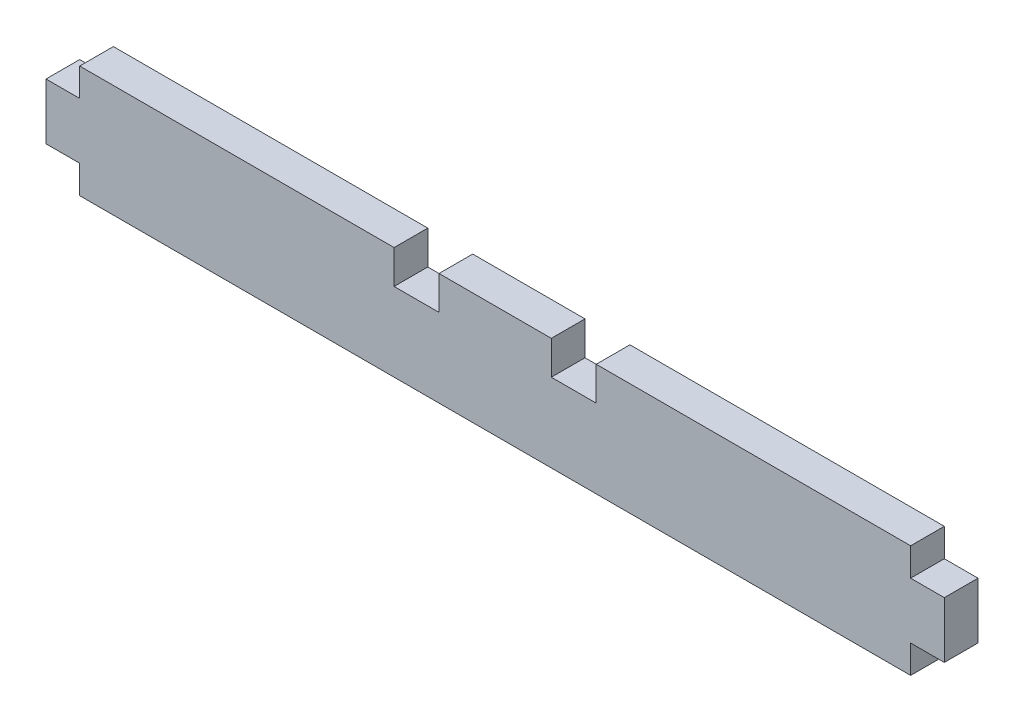
SolidWorks part; units mm, degrees
ref_plane "前基準面" through (0, 0, 0) normal (0, 0, 1) x (1, 0, 0)
ref_plane "上基準面" through (0, 0, 0) normal (0, 1, 0) x (1, 0, 0)
ref_plane "右基準面" through (0, 0, 0) normal (1, 0, 0) x (0, 0, -1)
sketch "草圖1" plane through (0, 0, 0) normal (0, 0, 1) x (1, 0, 0)
  line L0 (0, 0) -> (0, 13.235) construction
  line L1 (-37, 3.5) -> (37, 3.5)
  line L2 (-37, 3.5) -> (-37, -3.5)
  line L3 (-37, -3.5) -> (37, -3.5)
  line L4 (37, 3.5) -> (37, -3.5)
  line L5 (-37, 3.5) -> (37, -3.5) construction
  line L6 (-37, -3.5) -> (37, 3.5) construction
  line L7 (-5, 3.5) -> (5, 3.5)
  line L8 (-5, 3.5) -> (-5, 6.5)
  line L9 (-5, 6.5) -> (5, 6.5)
  line L10 (5, 3.5) -> (5, 6.5)
  line L11 (-37, 3.5) -> (-9, 3.5)
  line L12 (-37, 3.5) -> (-37, 6.5)
  line L13 (-37, 6.5) -> (-9, 6.5)
  line L14 (-9, 3.5) -> (-9, 6.5)
  line L15 (37, 3.5) -> (9, 3.5)
  line L16 (37, 3.5) -> (37, 6.5)
  line L17 (37, 6.5) -> (9, 6.5)
  line L18 (9, 3.5) -> (9, 6.5)
  line L19 (37, 4) -> (40, 4)
  line L20 (-37, -1) -> (-40, -1)
  line L21 (-37, -1) -> (-37, 4)
  line L22 (-37, 4) -> (-40, 4)
  line L23 (-40, -1) -> (-40, 4)
  line L24 (40, -1) -> (40, 4)
  line L25 (37, -1) -> (40, -1)
  line L26 (37, -1) -> (37, 4)
  point P0 (0, 0)
  point P10 (0, 6.5)
  point P23 (-37, 0)
  dimension "D1" = 74
  dimension "D2" = 7
  dimension "D3" = 3
  dimension "D4" = 10
  dimension "D5" = 4
  dimension "D6" = 3
  dimension "D7" = 4
  dimension "D8" = 3
  dimension "D9" = 5
  dimension "D10" = 2.5
extrude "填料-伸長1" add sketch "草圖1" along normal blind 3 contours L1 L14 L13 L12 | L4 L1 L2 L3 | L1 L10 L9 L8 | L18 L1 L16 L17 | L21 L20 L23 L22 | L19 L24 L25 L26
